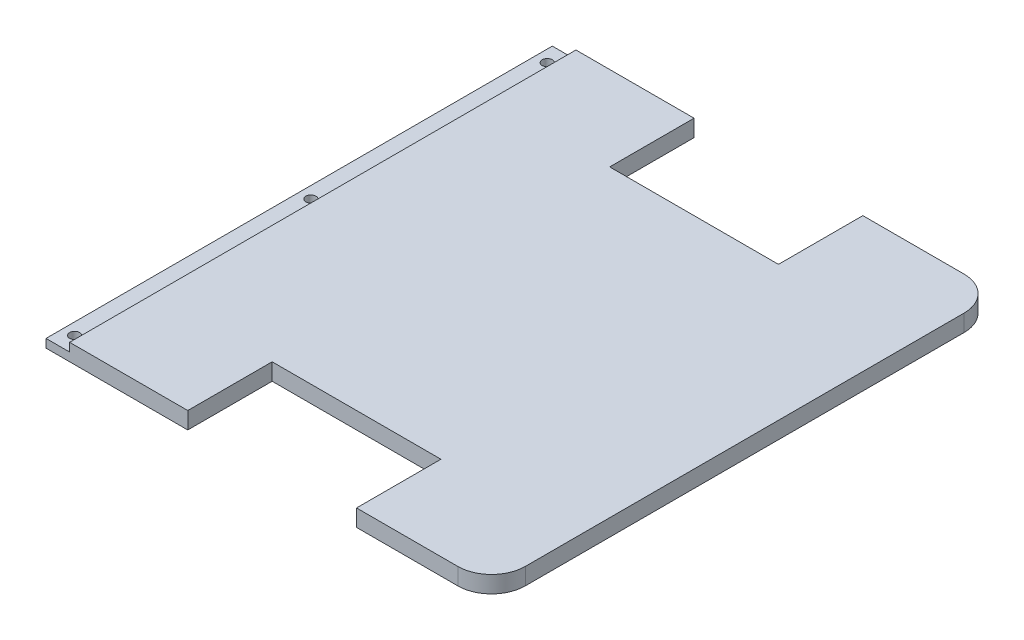
SolidWorks part; units mm, degrees
ref_plane "Front Plane" through (0, 0, 0) normal (0, 0, 1) x (1, 0, 0)
ref_plane "Top Plane" through (0, 0, 0) normal (0, 1, 0) x (1, 0, 0)
ref_plane "Right Plane" through (0, 0, 0) normal (1, 0, 0) x (0, 0, -1)
sketch "Sketch1" plane through (0, 0, 0) normal (0, 1, 0) x (1, 0, 0)
  line L0 (64.2704, 57.5107) -> (94.2704, 57.5107)
  line L1 (-135.7296, 57.5107) -> (-105.7296, 57.5107)
  line L2 (-145.7296, 47.5107) -> (-145.7296, -82.4893)
  line L3 (-135.7296, -92.4893) -> (-105.7296, -92.4893)
  line L4 (104.2704, 47.5107) -> (104.2704, -82.4893)
  line L6 (-105.7296, 57.5107) -> (-105.7296, 32.5107)
  line L7 (-105.7296, 32.5107) -> (-55.7296, 32.5107)
  line L8 (-55.7296, 57.5107) -> (-55.7296, 32.5107)
  line L10 (14.2704, 57.5107) -> (14.2704, 32.5107)
  line L11 (14.2704, 32.5107) -> (64.2704, 32.5107)
  line L12 (64.2704, 57.5107) -> (64.2704, 32.5107)
  line L13 (-105.7296, -67.4893) -> (-55.7296, -67.4893)
  line L14 (-105.7296, -67.4893) -> (-105.7296, -92.4893)
  line L16 (-55.7296, -67.4893) -> (-55.7296, -92.4893)
  line L17 (14.2704, -67.4893) -> (64.2704, -67.4893)
  line L18 (14.2704, -67.4893) -> (14.2704, -92.4893)
  line L20 (64.2704, -67.4893) -> (64.2704, -92.4893)
  line L21 (-55.7296, 57.5107) -> (14.2704, 57.5107)
  line L22 (-55.7296, -92.4893) -> (14.2704, -92.4893)
  line L23 (64.2704, -92.4893) -> (94.2704, -92.4893)
  arc A0 (94.2704, 57.5107) -> (104.2704, 47.5107) centre (94.2704, 47.5107) cw
  arc A1 (-145.7296, 47.5107) -> (-135.7296, 57.5107) centre (-135.7296, 47.5107) cw
  arc A2 (-145.7296, -82.4893) -> (-135.7296, -92.4893) centre (-135.7296, -82.4893) ccw
  arc A3 (94.2704, -92.4893) -> (104.2704, -82.4893) centre (94.2704, -82.4893) ccw
  point P24 (-145.7296, 57.5107)
  point P27 (-145.7296, -92.4893)
  point P30 (104.2704, -92.4893)
  dimension "D9" = 10
  dimension "D10" = 10
  dimension "D1" = 150
  dimension "D2" = 250
  dimension "D3" = 50
  dimension "D4" = 25
  dimension "D5" = 40
  dimension "D6" = 40
  dimension "D7" = 40
  dimension "D8" = 40
extrude "Boss-Extrude1" add sketch "Sketch1" along normal blind 5
sketch "Sketch2" plane through (0, 0, -57.5107) normal (0, 0, -1) x (-1, 0, 0)
  line L0 (20.7296, 2.5) -> (20.7296, 5)
  line L1 (-14.2704, 0) -> (55.7296, 0) construction
  line L2 (-14.2704, 5) -> (55.7296, 5) construction
  line L3 (27.7296, 0) -> (27.7296, 2.5)
  line L5 (27.7296, 2.5) -> (20.7296, 2.5)
  line L6 (55.7296, 0) -> (105.7296, 0) construction
  line L7 (105.7296, 5) -> (135.7296, 5) construction
  line L8 (105.7296, 0) -> (135.7296, 0) construction
  line L9 (135.7296, 0) -> (145.7296, 0) construction
  line L10 (145.7296, 5) -> (145.7296, 0) construction
  line L11 (145.7296, 5) -> (135.7296, 5) construction
  line L12 (55.7296, 5) -> (105.7296, 5) construction
  line L13 (55.7296, 0) -> (105.7296, 0)
  line L14 (105.7296, 5) -> (135.7296, 5)
  line L15 (105.7296, 0) -> (135.7296, 0)
  line L16 (135.7296, 0) -> (145.7296, 0)
  line L17 (145.7296, 5) -> (145.7296, 0)
  line L18 (145.7296, 5) -> (135.7296, 5)
  line L19 (55.7296, 5) -> (105.7296, 5)
  line L20 (27.7296, 0) -> (55.7296, 0)
  line L21 (20.7296, 5) -> (55.7296, 5)
  line L22 (20.7296, 0) -> (20.7296, 5) construction
  line L23 (27.7296, 0) -> (27.7296, 5) construction
  dimension "D1" = 7
extrude "Cut-Extrude1" cut sketch "Sketch2" against normal up to surface (150 mm away) up to face at (-20.7296, 2.5, 92.4893)
sketch "Sketch3" plane through (0, 2.5, 0) normal (0, 1, 0) x (1, 0, 0)
  line L0 (-20.7296, -92.4893) -> (-20.7296, 57.5107) construction
  line L1 (-20.7296, -92.4893) -> (-20.7296, 57.5107) construction
  circle A0 centre (-24.2296, -17.4893) radius 1.5
  circle A1 centre (-24.2296, 52.5107) radius 1.5
  circle A2 centre (-24.2296, -87.4893) radius 1.5
  point P4 (-20.7296, -17.4893)
  point P9 (0, 0)
  dimension "D1" = 3
  dimension "D2" = 3.5
  dimension "D3" = 70
  dimension "D4" = 70
extrude "Cut-Extrude2" cut sketch "Sketch3" against normal through all
